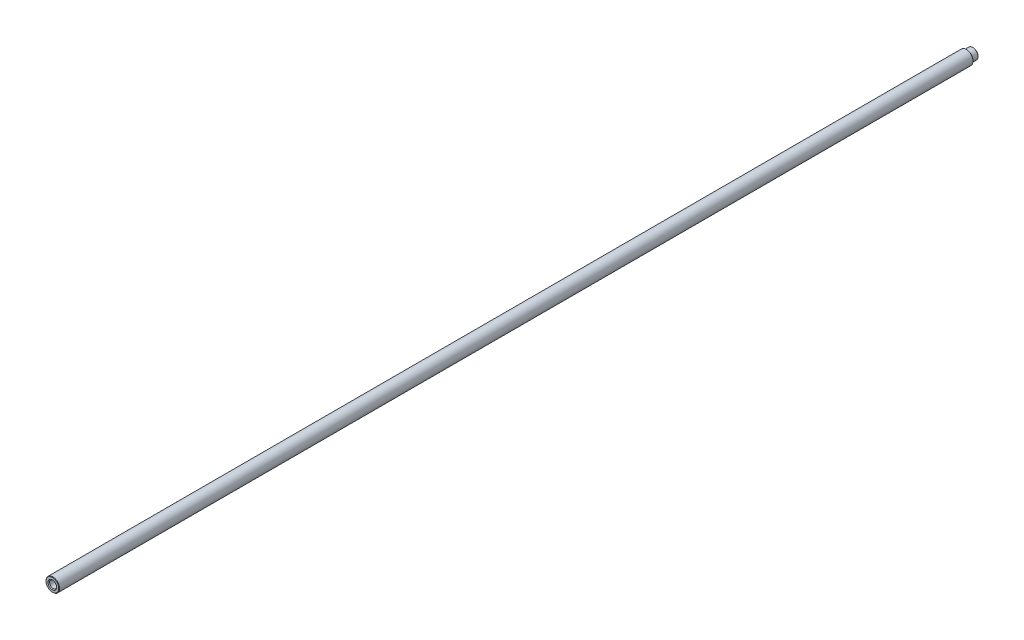
SolidWorks part; units mm, degrees
material "6063-T5"
ref_plane "Front Plane" through (0, 0, 0) normal (0, 0, 1) x (1, 0, 0)
ref_plane "Top Plane" through (0, 0, 0) normal (0, 1, 0) x (1, 0, 0)
ref_plane "Right Plane" through (0, 0, 0) normal (1, 0, 0) x (0, 0, -1)
ref_axis "Centre Axis" through (0, 0, -232.2463) along (0, 0, 1)
sketch "Sketch1" plane through (0, 0, 0) normal (0, 0, 1) x (1, 0, 0)
  circle A0 centre (0, 0) radius 3.175
  dimension "D1" = 6.35
extrude "Boss-Extrude1" add sketch "Sketch1" along normal mid plane 430
hole_wizard "M4x0.7 Tapped Hole1" positions "Sketch2" profile "Sketch4" tap size "M4x0.7" standard "ANSI Metric"
sketch "Sketch2" plane through (0, 0, -215) normal (0, 0, -1) x (-1, 0, 0)
  circle A1 centre (0, 0) radius 3.175 construction
  point P0 (0, 0)
sketch "Sketch4" plane through (0, 0, -215) normal (1, 0, 0) x (0, 1, 0)
  line L0 (0, 0) -> (0, 14.4914)
  line L1 (0, 14.4914) -> (1.65, 13.5)
  line L2 (1.65, 13.5) -> (1.65, 0.35)
  line L3 (1.65, 0.35) -> (2, 0)
  line L5 (2, 0) -> (0, 0)
  line L6 (-1.65, 0.35) -> (-2, 0) construction
  line L10 (0, 14.4914) -> (-1.65, 13.5) construction
  line L11 (0, -6.35) -> (0, 107.95) construction
  dimension "Tap Drill Dia." = 3.3
  dimension "Tap Drill Depth" = 13.5
  dimension "Near C'Sink Dia." = 4
  dimension "Near C'Sink Angle" = 90
  dimension "Drill Angle" = 118
hole_wizard "M4x0.7 Tapped Hole2" positions "Sketch5" profile "Sketch6" tap size "M4x0.7" standard "ANSI Metric"
sketch "Sketch5" plane through (0, 0, 215) normal (0, 0, 1) x (1, 0, 0)
  circle A2 centre (0, 0) radius 3.175 construction
  point P0 (0, 0)
sketch "Sketch6" plane through (0, 0, 215) normal (1, 0, 0) x (0, -1, 0)
  line L0 (0, 0) -> (0, 14.4914)
  line L1 (0, 14.4914) -> (1.65, 13.5)
  line L2 (1.65, 13.5) -> (1.65, 0.35)
  line L3 (1.65, 0.35) -> (2, 0)
  line L5 (2, 0) -> (0, 0)
  line L6 (-1.65, 0.35) -> (-2, 0) construction
  line L10 (0, 14.4914) -> (-1.65, 13.5) construction
  line L11 (0, -6.35) -> (0, 107.95) construction
  dimension "Tap Drill Dia." = 3.3
  dimension "Tap Drill Depth" = 13.5
  dimension "Near C'Sink Dia." = 4
  dimension "Near C'Sink Angle" = 90
  dimension "Drill Angle" = 118
sketch "Sketch7" plane through (0, 0, 0) normal (0, 1, 0) x (1, 0, 0)
  line L0 (3.175, -215) -> (3.175, 215) construction
  line L1 (2.5, 215) -> (3.175, 215)
  line L2 (2.5, 215) -> (2.5, 212)
  line L3 (2.5, 212) -> (3.175, 212)
  line L4 (3.175, 215) -> (3.175, 212)
  line L5 (2, 215) -> (-2, 215) construction
  line L6 (0, 221.2781) -> (0, 215.5418) construction
  line L7 (0, 232.2463) -> (0, -232.2463) construction
  dimension "D1" = 5
  dimension "D2" = 3
revolve "Cut-Revolve1" cut sketch "Sketch7" angle 360 about axis through (0, 0, -232.2463) along (0, 0, 1)
chamfer "Chamfer1" distance 0.2 angle 45 3 edges at (3.175, 0, 215) (-3.175, 0, -212) (-2.5, 0, -215)
